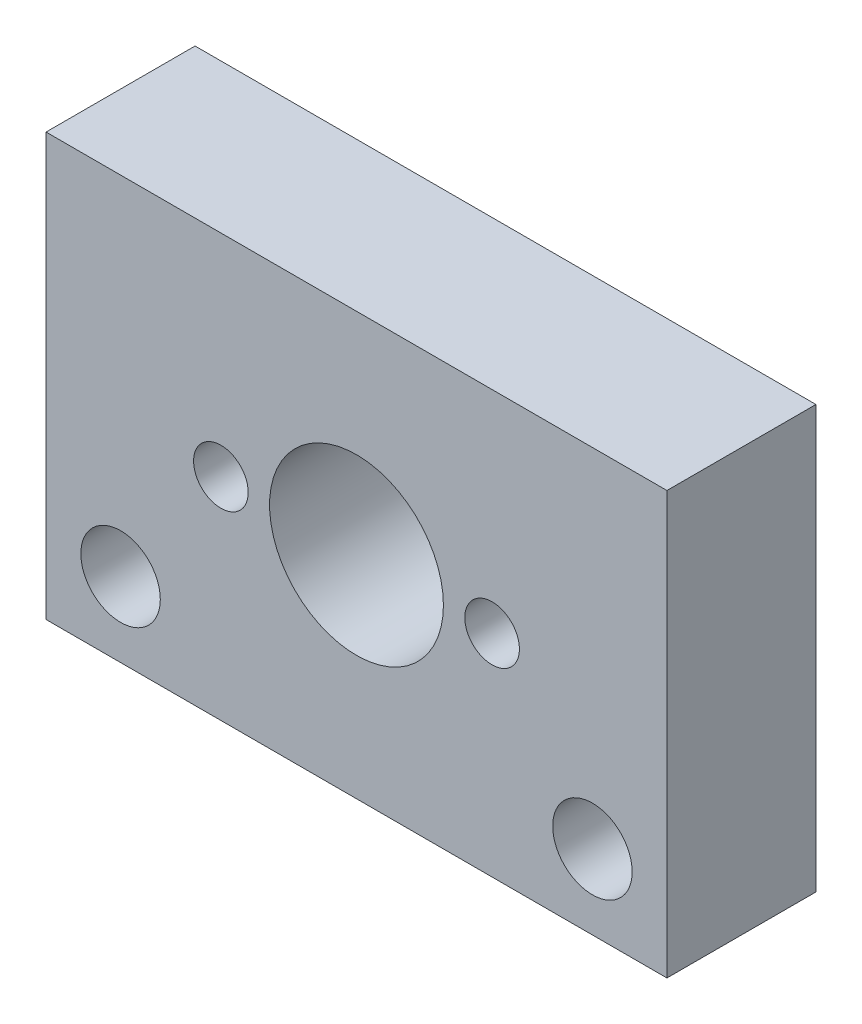
SolidWorks part; units mm, degrees
material "3.3547 (EN-AW 5083)"
ref_plane "Vorne" through (0, 0, 0) normal (0, 0, 1) x (1, 0, 0)
ref_plane "Oben" through (0, 0, 0) normal (0, 1, 0) x (1, 0, 0)
ref_plane "Rechts" through (0, 0, 0) normal (1, 0, 0) x (0, 0, -1)
sketch "Skizze1" plane through (0, 0, 0) normal (0, 0, 1) x (1, 0, 0)
  line L1 (-12.5, 8.5) -> (12.5, 8.5)
  line L2 (-12.5, 8.5) -> (-12.5, -8.5)
  line L3 (-12.5, -8.5) -> (12.5, -8.5)
  line L4 (12.5, 8.5) -> (12.5, -8.5)
  line L5 (-12.5, 8.5) -> (12.5, -8.5) construction
  line L6 (-12.5, -8.5) -> (12.5, 8.5) construction
  point P0 (0, 0)
  dimension "D1" = 25
  dimension "D2" = 17
extrude "Aufsatz-Linear austragen1" add sketch "Skizze1" along normal blind 6
hole_wizard "Ø3.2 (3.2) Durchmesser Bohrung1" positions "Skizze2" profile "Skizze3" hole size "Ø3.2" standard "DIN" end condition through all
sketch "Skizze2" plane through (0, 0, 6) normal (0, 0, 1) x (1, 0, 0)
  line L0 (-12.5, -8.5) -> (12.5, -8.5) construction
  line L1 (-12.5, 8.5) -> (-12.5, -8.5) construction
  point P0 (-9.5, -5.5)
  point P2 (9.5, -5.5)
  dimension "D1" = 3
  dimension "D2" = 3
  dimension "D3" = 22
sketch "Skizze3" plane through (-9.5, -5.5, 6) normal (1, 0, 0) x (0, -1, 0)
  line L0 (0, 0) -> (0, 6)
  line L1 (0, 6) -> (1.6, 6)
  line L2 (1.6, 6) -> (1.6, 0)
  line L5 (1.6, 0) -> (0, 0)
  line L11 (0, -6.35) -> (0, 107.95) construction
  dimension "Bohrerdurchmesser" = 3.2
  dimension "Bohrungstiefe" = 6
hole_wizard "Ø7.0 (7) Durchmesser Bohrung1" positions "Skizze4" profile "Skizze5" hole size "Ø7.0" standard "DIN" end condition through all
sketch "Skizze4" plane through (0, 0, 6) normal (0, 0, 1) x (1, 0, 0)
  line L0 (0, -3.355) -> (0, 3.355) construction
  line L1 (-12.5, -8.5) -> (12.5, -8.5) construction
  point P0 (0, 0)
  dimension "D1" = 8.5
sketch "Skizze5" plane through (0, 0, 6) normal (1, 0, 0) x (0, -1, 0)
  line L0 (0, 0) -> (0, 6)
  line L1 (0, 6) -> (3.5, 6)
  line L2 (3.5, 6) -> (3.5, 0)
  line L5 (3.5, 0) -> (0, 0)
  line L11 (0, -6.35) -> (0, 107.95) construction
  dimension "Bohrerdurchmesser" = 7
  dimension "Bohrungstiefe" = 6
hole_wizard "Ø2.2 (2.2) Durchmesser Bohrung1" positions "Skizze6" profile "Skizze7" hole size "Ø2.2" standard "DIN" end condition through all
sketch "Skizze6" plane through (0, 0, 6) normal (0, 0, 1) x (1, 0, 0)
  line L0 (3.355, 0) -> (-3.355, 0) construction
  line L3 (0, -3.355) -> (0, 3.355) construction
  point P0 (-5.46, 0)
  point P4 (5.46, 0)
  dimension "D1" = 5.46
  dimension "D2" = 10.92
sketch "Skizze7" plane through (-5.46, 0, 6) normal (1, 0, 0) x (0, -1, 0)
  line L0 (0, 0) -> (0, 6)
  line L1 (0, 6) -> (1.1, 6)
  line L2 (1.1, 6) -> (1.1, 0)
  line L5 (1.1, 0) -> (0, 0)
  line L11 (0, -6.35) -> (0, 107.95) construction
  dimension "Bohrerdurchmesser" = 2.2
  dimension "Bohrungstiefe" = 6
